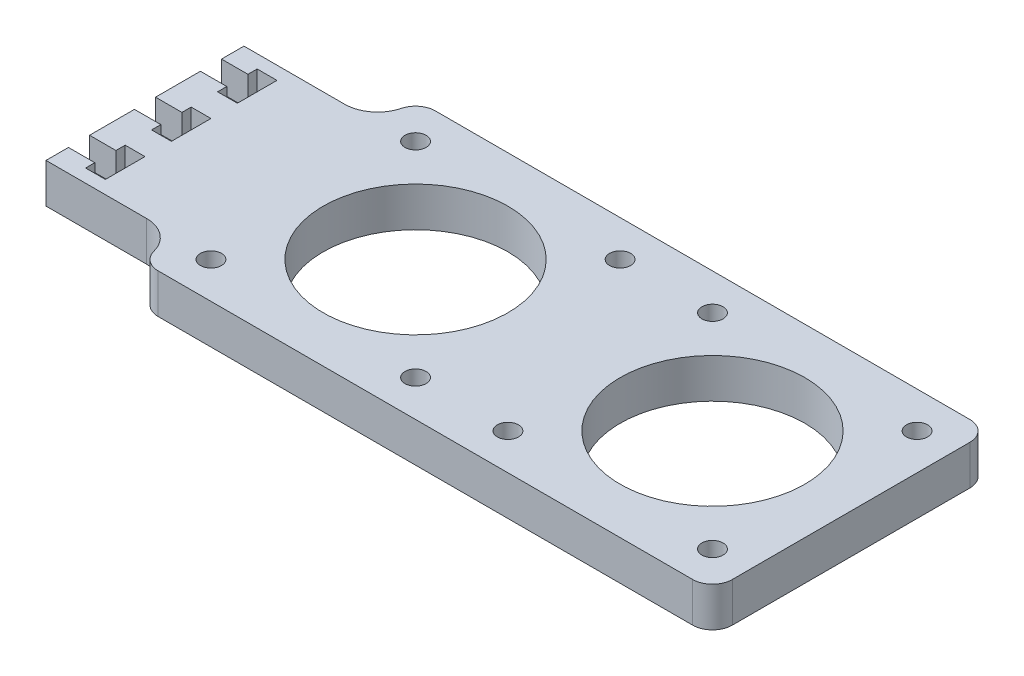
SolidWorks part; units mm, degrees
ref_plane "前视基准面" through (0, 0, 0) normal (0, 0, 1) x (1, 0, 0)
ref_plane "上视基准面" through (0, 0, 0) normal (0, 1, 0) x (1, 0, 0)
ref_plane "右视基准面" through (0, 0, 0) normal (1, 0, 0) x (0, 0, -1)
other "Configuration Table"
sketch "草图1" plane through (0, 0, 0) normal (0, 1, 0) x (1, 0, 0)
  line L1 (0, 0) -> (20, 0)
  line L2 (0, 0) -> (0, 30)
  line L3 (0, 30) -> (20, 30)
  line L4 (20, 0) -> (20, 30)
  dimension "D1" = 30
  dimension "D2" = 20
extrude "凸台-拉伸1" add sketch "草图1" along normal blind 6
sketch "草图2" plane through (0, 6, 0) normal (0, 1, 0) x (1, 0, 0)
  line L0 (0, 30) -> (0, 0) construction
  line L1 (0, 3.4) -> (4, 3.4)
  line L2 (0, 3.4) -> (0, 6.6)
  line L3 (0, 6.6) -> (4, 6.6)
  line L4 (4, 3.4) -> (4, 6.6)
  line L5 (0, 0) -> (20, 0) construction
  line L6 (0, 16.6) -> (4, 16.6)
  line L7 (0, 13.4) -> (0, 16.6)
  line L8 (4, 13.4) -> (4, 16.6)
  line L9 (0, 13.4) -> (4, 13.4)
  line L10 (0, 26.6) -> (4, 26.6)
  line L11 (0, 23.4) -> (0, 26.6)
  line L12 (4, 23.4) -> (4, 26.6)
  line L13 (0, 23.4) -> (4, 23.4)
  dimension "D1" = 3.4
  dimension "D2" = 3.2
  dimension "D3" = 4
  dimension "D4" = 3
extrude "切除-拉伸1" cut sketch "草图2" against normal blind 4.5
sketch "草图3" plane through (0, 6, 0) normal (0, 1, 0) x (1, 0, 0)
  line L0 (0, 0) -> (20, 0) construction
  line L1 (4, 2) -> (7, 2)
  line L2 (4, 2) -> (4, 8)
  line L3 (4, 8) -> (7, 8)
  line L4 (7, 2) -> (7, 8)
  line L5 (4, 12) -> (4, 18)
  line L6 (4, 18) -> (7, 18)
  line L7 (7, 12) -> (7, 18)
  line L8 (4, 12) -> (7, 12)
  line L9 (4, 22) -> (4, 28)
  line L10 (4, 28) -> (7, 28)
  line L11 (7, 22) -> (7, 28)
  line L12 (4, 22) -> (7, 22)
  point P7 (5.5, 2)
  dimension "D1" = 3
  dimension "D2" = 6
  dimension "D3" = 2
  dimension "D4" = 3
extrude "切除-拉伸2" cut sketch "草图3" against normal blind 14.5
sketch "草图4" plane through (0, 0, 0) normal (0, -1, 0) x (1, 0, 0)
  line L0 (20, 0) -> (20, -30) construction
  line L1 (20, 6) -> (107, 6)
  line L2 (20, 6) -> (20, -36)
  line L3 (20, -36) -> (107, -36)
  line L4 (107, 6) -> (107, -36)
  line L5 (20, 6) -> (107, -36) construction
  line L6 (20, -36) -> (107, 6) construction
  line L7 (20, -30) -> (0, -30) construction
  line L8 (20, -15) -> (50020, -15) construction
  line L9 (41, 3.3044) -> (41, 50003.3044) construction
  line L10 (63.5, -15) -> (63.5, 49985) construction
  line L11 (86, -15) -> (86, -50015) construction
  circle A0 centre (25.5, 0.5) radius 1.6
  circle A1 centre (25.5, -30.5) radius 1.6
  circle A2 centre (56.5, -30.5) radius 1.6
  circle A3 centre (56.5, 0.5) radius 1.6
  circle A4 centre (41, -15) radius 14
  circle A6 centre (86, -15) radius 14
  circle A7 centre (70.5, 0.5) radius 1.6
  circle A8 centre (101.5, 0.5) radius 1.6
  circle A9 centre (101.5, -30.5) radius 1.6
  circle A10 centre (70.5, -30.5) radius 1.6
  point P0 (63.5, -15)
  point P13 (20, -15)
  point P34 (70.4412, -8.7123)
  dimension "D3" = 5.5
  dimension "D4" = 3.2
  dimension "D5" = 5.5
  dimension "D9" = 45
  dimension "D10" = 28
  dimension "D11" = 28
  dimension "D12" = 15.5
  dimension "D13" = 15.5
  dimension "D14" = 3.2
  dimension "D1" = 42
  dimension "D2" = 6
  dimension "D7" = 87
  dimension "D8" = 21
  dimension "D6" = 2
extrude "凸台-拉伸2" add sketch "草图4" against normal blind 6
fillet "圆角1" radius 3 4 edges at (20, 3, 6) (20, 3, -36) (107, 3, -36) (107, 3, 6)
fillet "圆角2" radius 5 2 edges at (20, 3, -30) (20, 3, 0)
